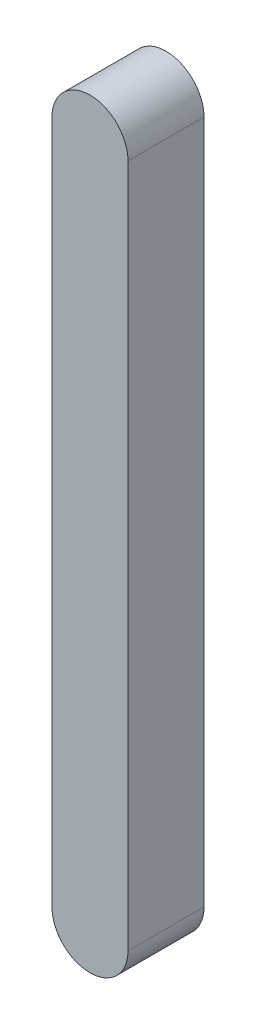
SolidWorks part; units mm, degrees
ref_plane "Plan de face" through (0, 0, 0) normal (0, 0, 1) x (1, 0, 0)
ref_plane "Plan de dessus" through (0, 0, 0) normal (0, 1, 0) x (1, 0, 0)
ref_plane "Plan de droite" through (0, 0, 0) normal (1, 0, 0) x (0, 0, -1)
sketch "Esquisse1" plane through (0, 0, 0) normal (0, 1, 0) x (1, 0, 0)
  line L1 (-12.5, 12.5) -> (12.5, 12.5)
  line L2 (-12.5, 12.5) -> (-12.5, -12.5)
  line L3 (-12.5, -12.5) -> (12.5, -12.5)
  line L4 (12.5, 12.5) -> (12.5, -12.5)
  dimension "D1" = 25
  dimension "D2" = 12.5
  dimension "D3" = 12.5
extrude "Boss.-Extru.1" add sketch "Esquisse1" along normal blind 225
sketch "Esquisse2" plane through (0, 0, 12.5) normal (0, 0, 1) x (1, 0, 0)
  line L0 (-12.5, 225) -> (12.5, 225) construction
  line L1 (-12.5, 225) -> (12.5, 225)
  arc A0 (12.5, 225) -> (-12.5, 225) centre (0, 225) ccw
  dimension "D1" = 12.5
extrude "Boss.-Extru.2" add sketch "Esquisse2" against normal up to surface (25 mm away) up to face at (0, 112.5, -12.5)
sketch "Esquisse3" plane through (0, 0, 12.5) normal (0, 0, 1) x (1, 0, 0)
  line L0 (-12.5, 0) -> (12.5, 0) construction
  line L1 (-12.5, 0) -> (12.5, 0)
  arc A0 (-12.5, 0) -> (12.5, 0) centre (0, 0) ccw
extrude "Boss.-Extru.3" add sketch "Esquisse3" against normal up to surface (25 mm away) up to face at (0, 115.625, -12.5)
